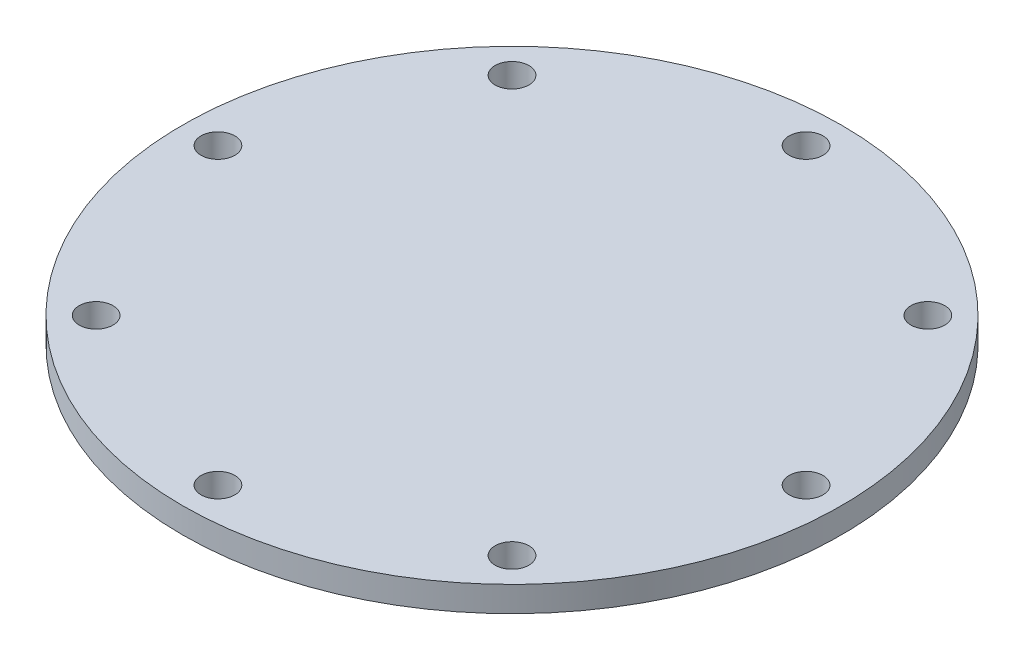
SolidWorks part; units mm, degrees
ref_plane "前视基准面" through (0, 0, 0) normal (0, 0, 1) x (1, 0, 0)
ref_plane "上视基准面" through (0, 0, 0) normal (0, 1, 0) x (1, 0, 0)
ref_plane "右视基准面" through (0, 0, 0) normal (1, 0, 0) x (0, 0, -1)
sketch "草图1" plane through (0, 0, 0) normal (0, 1, 0) x (1, 0, 0)
  circle A1 centre (0, 0) radius 195
  dimension "D1" = 390
extrude "凸台-拉伸1" add sketch "草图1" along normal blind 15
sketch "草图2" plane through (0, 15, 0) normal (0, 1, 0) x (1, 0, 0)
  circle A0 centre (0, 0) radius 174 construction
  circle A1 centre (-174, 0) radius 10
  circle A2 centre (-123.0366, 123.0366) radius 10
  circle A3 centre (0, 174) radius 10
  circle A4 centre (123.0366, 123.0366) radius 10
  circle A5 centre (174, 0) radius 10
  circle A6 centre (123.0366, -123.0366) radius 10
  circle A7 centre (0, -174) radius 10
  circle A8 centre (-123.0366, -123.0366) radius 10
  dimension "D1" = 348
  dimension "D2" = 20
  dimension "D3" = 8
extrude "切除-拉伸1" cut sketch "草图2" against normal up to next
